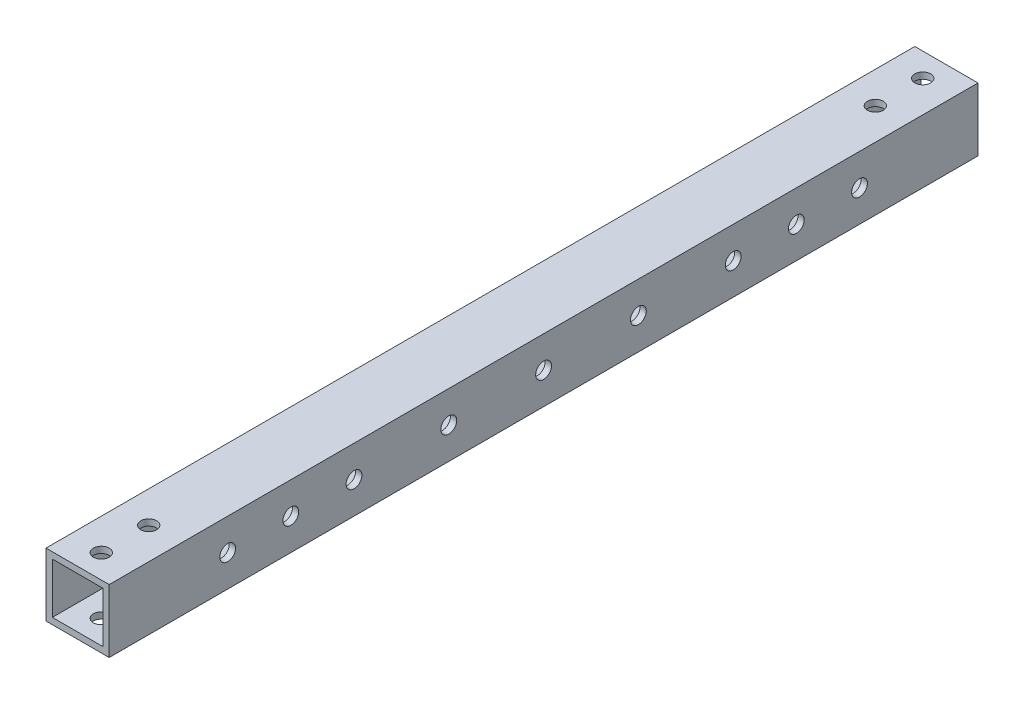
SolidWorks part; units mm, degrees
material "6063-T5"
ref_plane "前视基准面" through (0, 0, 0) normal (0, 0, 1) x (1, 0, 0)
ref_plane "上视基准面" through (0, 0, 0) normal (0, 1, 0) x (1, 0, 0)
ref_plane "右视基准面" through (0, 0, 0) normal (1, 0, 0) x (0, 0, -1)
sketch "草图1" plane through (0, 0, 0) normal (0, 0, 1) x (1, 0, 0)
  line L1 (-10, 10) -> (10, 10)
  line L2 (-10, 10) -> (-10, -10)
  line L3 (-10, -10) -> (10, -10)
  line L4 (10, 10) -> (10, -10)
  line L5 (-10, 10) -> (10, -10) construction
  line L6 (-10, -10) -> (10, 10) construction
  line L7 (-8, 8) -> (8, 8)
  line L8 (-8, 8) -> (-8, -8)
  line L9 (-8, -8) -> (8, -8)
  line L10 (8, 8) -> (8, -8)
  line L11 (-8, 8) -> (8, -8) construction
  line L12 (-8, -8) -> (8, 8) construction
  point P0 (0, 0)
  point P5 (0, 0)
  point P11 (8, 0)
  dimension "D1" = 20
  dimension "D2" = 20
  dimension "D3" = 2
  dimension "D4" = 2
extrude "凸台-拉伸1" add sketch "草图1" along normal blind 275
sketch "草图4" plane through (-10, 0, 0) normal (-1, 0, 0) x (0, 0, 1)
  line L0 (137.5, 28.5228) -> (137.5, -37.6675) construction
  line L1 (0, 10) -> (0, -10) construction
  line L2 (275, 10) -> (275, -10) construction
  line L3 (107.5, 0) -> (137.5, 0) construction
  circle A0 centre (107.5, 0) radius 2.5
  circle A1 centre (167.5, 0) radius 2.5
  circle A2 centre (137.5, 0) radius 2.5
  dimension "D2" = 5
  dimension "D1" = 5
  dimension "D3" = 30
extrude "切除-拉伸3" cut sketch "草图4" against normal blind 84
sketch "草图5" plane through (10, 0, 0) normal (1, 0, 0) x (0, 0, -1)
  line L1 (-137.5, 10) -> (-137.5, -84.544) construction
  line L2 (-275, 10) -> (0, 10) construction
  line L3 (0, 0) -> (-77.5, 0) construction
  circle A0 centre (-77.5, 0) radius 2.5
  circle A1 centre (-57.5, 0) radius 2.5
  circle A2 centre (-37.5, 0) radius 2.5
  circle A3 centre (-237.5, 0) radius 2.5
  circle A4 centre (-217.5, 0) radius 2.5
  circle A5 centre (-197.5, 0) radius 2.5
  dimension "D1" = 5
  dimension "D3" = 20
  dimension "D4" = 20
  dimension "D5" = 60
extrude "切除-拉伸4" cut sketch "草图5" against normal through all
sketch "草图6" plane through (0, 10, 0) normal (0, 1, 0) x (1, 0, 0)
  line L0 (0, 0) -> (0, -275) construction
  line L1 (10, -275) -> (-10, -275) construction
  line L2 (10, 0) -> (-10, 0) construction
  circle A0 centre (0, -267.5) radius 2.5
  circle A1 centre (0, -252.5) radius 2.5
  circle A2 centre (0, -22.5) radius 2.5
  circle A3 centre (0, -7.5) radius 2.5
  dimension "D1" = 15
  dimension "D2" = 7.5
  dimension "D3" = 5
  dimension "D4" = 5
  dimension "D5" = 5
  dimension "D6" = 5
  dimension "D7" = 7.5
  dimension "D8" = 15
extrude "切除-拉伸5" cut sketch "草图6" against normal blind 20
